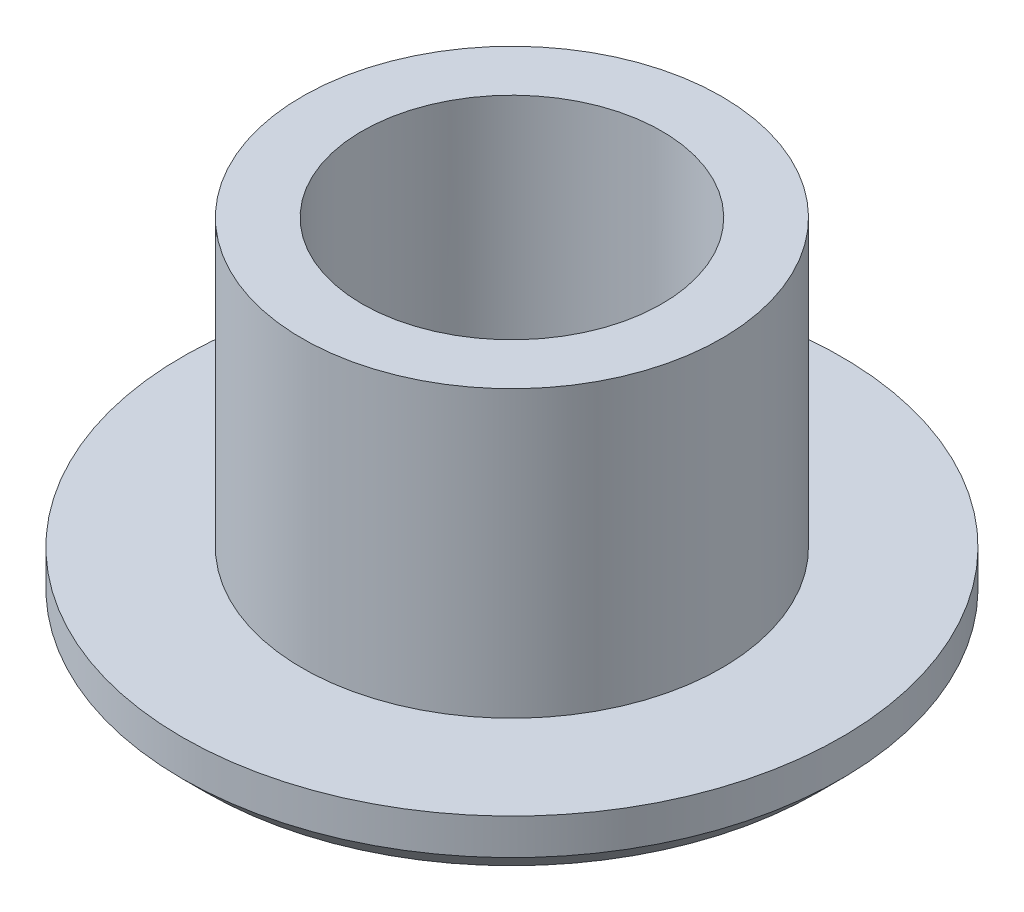
SolidWorks part; units mm, degrees
ref_plane "Front Plane" through (0, 0, 0) normal (0, 0, 1) x (1, 0, 0)
ref_plane "Top Plane" through (0, 0, 0) normal (0, 1, 0) x (1, 0, 0)
ref_plane "Right Plane" through (0, 0, 0) normal (1, 0, 0) x (0, 0, -1)
sketch "Sketch1" plane through (0, 0, 0) normal (0, 1, 0) x (1, 0, 0)
  circle A0 centre (0, 0) radius 5.5
  dimension "D1" = 11
extrude "Boss-Extrude1" add sketch "Sketch1" along normal blind 1
sketch "Sketch2" plane through (0, 1, 0) normal (0, 1, 0) x (1, 0, 0)
  circle A0 centre (0, 0) radius 3.5
  dimension "D1" = 7
extrude "Boss-Extrude2" add sketch "Sketch2" along normal blind 4.7625
sketch "Sketch3" plane through (0, 5.7625, 0) normal (0, 1, 0) x (1, 0, 0)
  circle A0 centre (0, 0) radius 2.5
  dimension "D1" = 5
extrude "Cut-Extrude1" cut sketch "Sketch3" against normal through all
chamfer "Chamfer1" distance 0.4 angle 45 2 edges at (0, 0, 5.5) (0, 0, 2.5)
